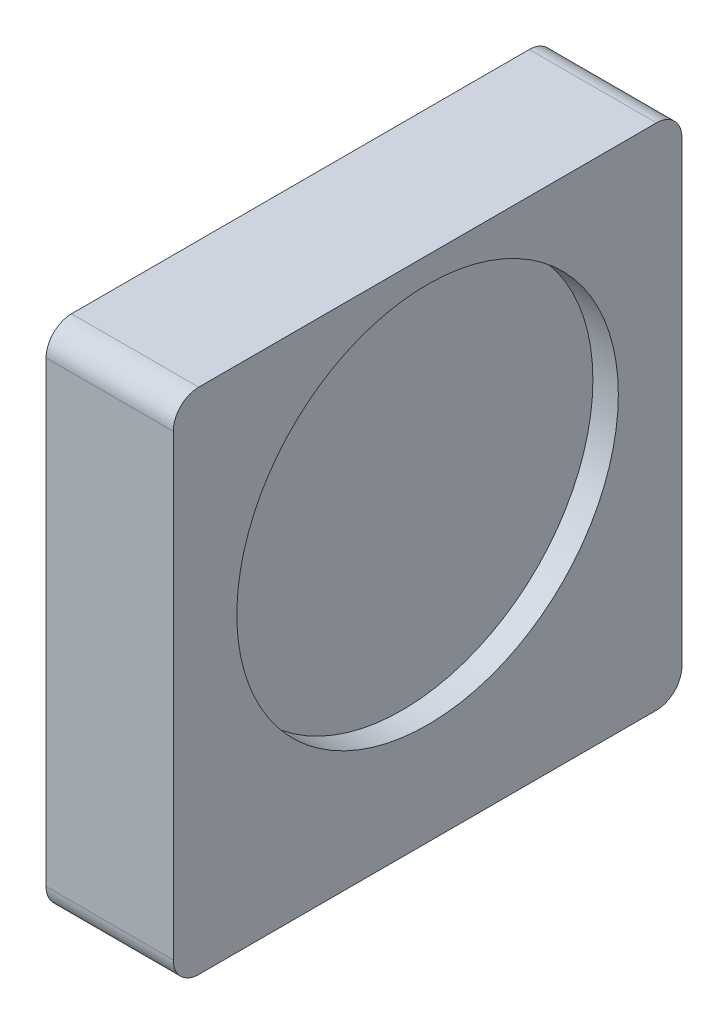
SolidWorks part; units mm, degrees
ref_plane "Front Plane" through (0, 0, 0) normal (1, 0, 0) x (0, 1, 0)
ref_plane "Top Plane" through (0, 0, 0) normal (0, 0, 1) x (0, 1, 0)
ref_plane "Right Plane" through (0, 0, 0) normal (0, 1, 0) x (-1, 0, 0)
sketch "Sketch1" plane through (0, 0, 0) normal (1, 0, 0) x (0, 1, 0)
  line L1 (-20, 20) -> (20, 20)
  line L2 (-20, 20) -> (-20, -20)
  line L3 (-20, -20) -> (20, -20)
  line L4 (20, 20) -> (20, -20)
  line L5 (-20, 20) -> (20, -20) construction
  line L6 (-20, -20) -> (20, 20) construction
  point P0 (0, 0)
  dimension "D1" = 40
  dimension "D2" = 40
extrude "Boss-Extrude1" add sketch "Sketch1" along normal blind 10
sketch "Sketch2" plane through (10, 0, 0) normal (1, 0, 0) x (0, 1, 0)
  line L0 (20, -20) -> (20, 20) construction
  line L1 (-20, -20) -> (20, -20) construction
  circle A0 centre (3, 0) radius 15
  dimension "D1" = 30
  dimension "D2" = 17
  dimension "D3" = 20
extrude "Cut-Extrude1" cut sketch "Sketch2" against normal blind 2
fillet "Fillet1" radius 2 4 edges at (5, 20, 20) (5, 20, -20) (5, -20, -20) (5, -20, 20)
